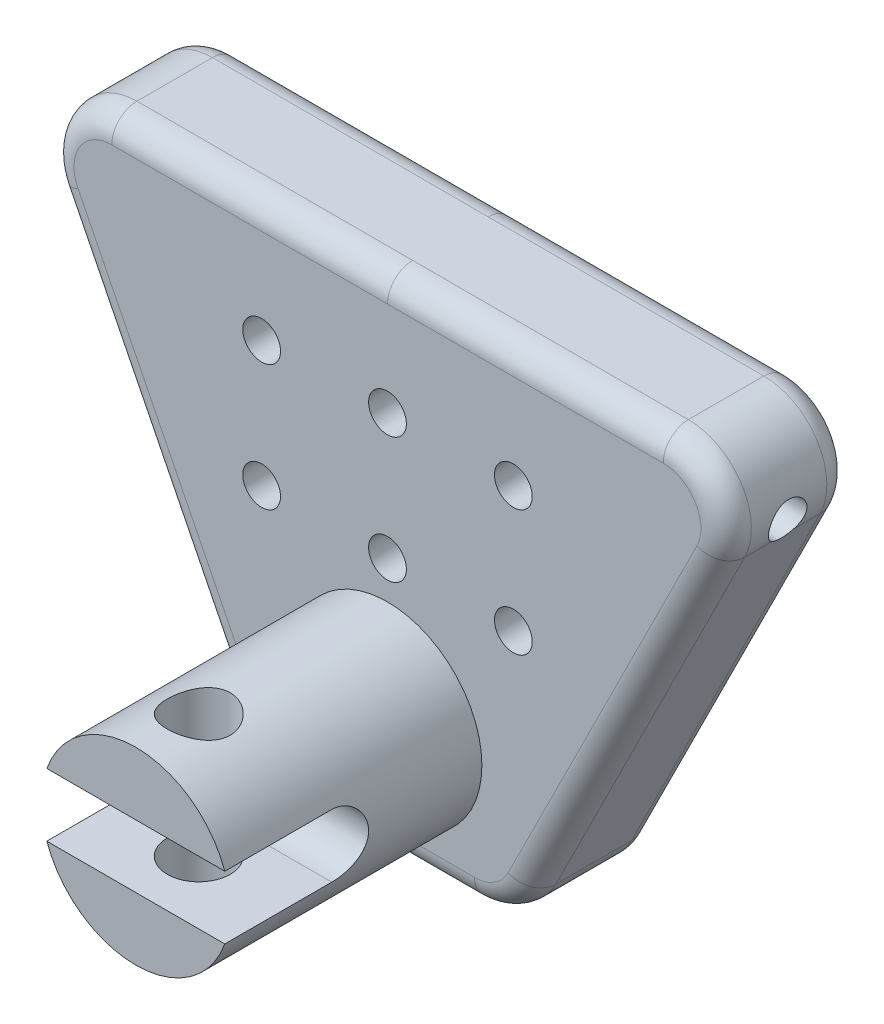
SolidWorks part; units mm, degrees
ref_plane "Front Plane" through (0, 0, 0) normal (0, 0, 1) x (1, 0, 0)
ref_plane "Top Plane" through (0, 0, 0) normal (0, 1, 0) x (1, 0, 0)
ref_plane "Right Plane" through (0, 0, 0) normal (1, 0, 0) x (0, 0, -1)
sketch "Sketch1" plane through (0, 0, 0) normal (0, 0, 1) x (1, 0, 0)
  line L0 (0, 0) -> (10, 0)
  line L1 (10, 0) -> (30, 40)
  line L2 (30, 40) -> (0, 40)
  line L3 (0, 40) -> (0, 0)
  dimension "D1" = 30
  dimension "D2" = 10
  dimension "D3" = 40
extrude "Boss-Extrude1" add sketch "Sketch1" along normal blind 10
fillet "Fillet1" radius 5 1 edges at (30, 40, 5)
fillet "Fillet2" radius 5 1 edges at (10, 0, 5)
fillet "Fillet3" radius 2 5 edges at (3.4549, 0, 10) (9.5385, 0.7467, 10) (10.9549, 40, 10) (26.1631, 37.6287, 10) (18.882, 17.7639, 10)
fillet "Fillet4" radius 2 5 edges at (3.4549, 0, 0) (9.5385, 0.7467, 0) (10.9549, 40, 0) (26.1631, 37.6287, 0) (18.882, 17.7639, 0)
mirror "Mirror1" about plane through (0, 0, 0) normal (1, 0, 0) of "Boss-Extrude1"
fillet "Fillet5" radius 5 1 edges at (-30, 40, 5)
fillet "Fillet6" radius 5 1 edges at (-10, 0, 5)
fillet "Fillet7" radius 2 5 edges at (-3.4549, 0, 0) (-9.5385, 0.7467, 0) (-10.9549, 40, 0) (-26.1631, 37.6287, 0) (-18.882, 17.7639, 0)
fillet "Fillet8" radius 2 5 edges at (-3.4549, 0, 10) (-9.5385, 0.7467, 10) (-10.9549, 40, 10) (-26.1631, 37.6287, 10) (-18.882, 17.7639, 10)
sketch "Sketch2" plane through (0, 0, 10) normal (0, 0, 1) x (1, 0, 0)
  line L0 (0, 0) -> (0, 40) construction
  circle A0 centre (0, 10) radius 7.5
  dimension "D1" = 15
  dimension "D2" = 10
extrude "Boss-Extrude2" add sketch "Sketch2" along normal blind 20
sketch "Sketch4" plane through (0, 0, 0) normal (1, 0, 0) x (0, 0, -1)
  line L0 (-30, 10) -> (-27.5, 10) construction
  line L1 (-30, 17.5) -> (-30, 2.5) construction
  line L2 (-10, 17.5) -> (-10, 2.5) construction
  line L3 (-21.5, 12.5) -> (-30, 12.5)
  line L4 (-21.5, 7.5) -> (-30, 7.5)
  line L5 (-30, 7.5) -> (-30, 12.5)
  line L6 (-19, 10) -> (-10, 10) construction
  arc A0 (-21.5, 7.5) -> (-21.5, 12.5) centre (-21.5, 10) ccw
  dimension "D2" = 5
  dimension "D1" = 8.5
extrude "Cut-Extrude1" cut sketch "Sketch4" against normal through all
mirror "Mirror2" about plane through (0, 0, 0) normal (1, 0, 0) of "Cut-Extrude1"
sketch "Sketch5" plane through (0, 0, 0) normal (0, 1, 0) x (1, 0, 0)
  line L0 (0, 0) -> (0, -30) construction
  line L1 (-7.0711, -30) -> (7.0711, -30) construction
  circle A0 centre (0, -25) radius 2.5
  dimension "D1" = 5
  dimension "D2" = 5
extrude "Cut-Extrude3" cut sketch "Sketch5" along normal through all
sketch "Sketch11" plane through (0, 0, 0) normal (0, 0, -1) x (-1, 0, 0)
  line L0 (0, 0) -> (0, 40) construction
  line L1 (0, 40) -> (0, 38) construction
  circle A0 centre (0, 30.5012) radius 1.5
  circle A1 centre (-10, 30.5012) radius 1.5
  circle A2 centre (10, 30.5012) radius 1.5
  circle A3 centre (0, 20.5012) radius 1.5
  circle A4 centre (10, 20.5012) radius 1.5
  circle A5 centre (-10, 20.5012) radius 1.5
  dimension "D1" = 3
  dimension "D2" = 2
  dimension "D3" = 2
  dimension "D4" = 2
  dimension "D5" = 2
  dimension "D6" = 2
extrude "Cut-Extrude6" cut sketch "Sketch11" against normal through all
sketch "Sketch12" plane through (0, 0, 0) normal (1, 0, 0) x (0, 0, -1)
  line L1 (-10, 3.6584) -> (-10, 33.6584) construction
  line L2 (-8, 40) -> (-2, 40) construction
  circle A0 centre (-5, 34) radius 1.5
  dimension "D1" = 3
  dimension "D2" = 5
  dimension "D3" = 6
extrude "Cut-Extrude7" cut sketch "Sketch12" against normal through all
mirror "Mirror3" about plane through (0, 0, 0) normal (1, 0, 0) of "Cut-Extrude7"
